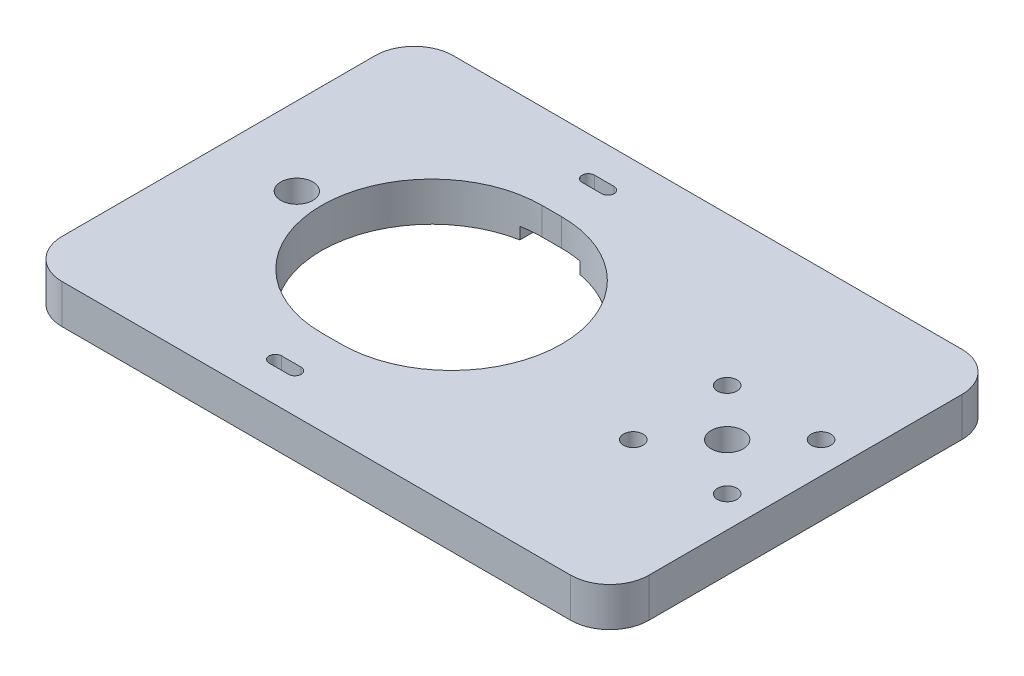
SolidWorks part; units mm, degrees
ref_plane "正面" through (0, 0, 0) normal (0, 0, 1) x (1, 0, 0)
ref_plane "平面" through (0, 0, 0) normal (0, 1, 0) x (1, 0, 0)
ref_plane "右側面" through (0, 0, 0) normal (1, 0, 0) x (0, 0, -1)
sketch "ｽｹｯﾁ1" plane through (0, 0, 0) normal (0, 1, 0) x (1, 0, 0)
  line L1 (-65, -50) -> (65, -50)
  line L2 (-75, -40) -> (-75, 40)
  line L3 (-65, 50) -> (65, 50)
  line L4 (75, -40) -> (75, 40)
  line L5 (-75, -50) -> (75, 50) construction
  line L6 (-75, 50) -> (75, -50) construction
  circle A0 centre (55, 0) radius 4.1
  circle A1 centre (43, 12) radius 2.5
  circle A2 centre (67, 12) radius 2.5
  circle A3 centre (67, -12) radius 2.5
  circle A4 centre (43, -12) radius 2.5
  arc A5 (65, 50) -> (75, 40) centre (65, 40) cw
  arc A6 (65, -50) -> (75, -40) centre (65, -40) ccw
  arc A7 (-65, -50) -> (-75, -40) centre (-65, -40) cw
  arc A8 (-75, 40) -> (-65, 50) centre (-65, 40) cw
  circle A9 centre (-55, 0) radius 4.1
  point P0 (0, 0)
  dimension "D3" = 8.2
  dimension "D9" = 5
  dimension "D10" = 10
  dimension "D11" = 8.2
  dimension "D1" = 150
  dimension "D2" = 100
  dimension "D4" = 20
  dimension "D5" = 24
  dimension "D6" = 24
  dimension "D7" = 12
  dimension "D8" = 12
  dimension "D12" = 20
extrude "ﾎﾞｽ - 押し出し1" add sketch "ｽｹｯﾁ1" along normal blind 10
sketch "ｽｹｯﾁ5" plane through (0, 10, 0) normal (0, 1, 0) x (1, 0, 0)
  line L0 (-27.5, 0) -> (-22.5, 0) construction
  line L3 (-20.5, 0) -> (-15.5, 0) construction
  line L6 (-20.5, 28.2) -> (-15.5, 28.2)
  line L9 (-20.5, -28.2) -> (-15.5, -28.2)
  line L10 (-20.5, 40) -> (-15.5, 40) construction
  line L11 (-20.5, 41.6) -> (-15.5, 41.6)
  line L12 (-20.5, 38.4) -> (-15.5, 38.4)
  line L13 (-20.5, -40) -> (-15.5, -40) construction
  line L14 (-20.5, -38.4) -> (-15.5, -38.4)
  line L15 (-20.5, -41.6) -> (-15.5, -41.6)
  circle A7 centre (-55, 0) radius 4.1 construction
  arc A9 (-20.5, 28.2) -> (-20.5, -28.2) centre (-20.5, 0) ccw
  arc A10 (-15.5, -28.2) -> (-15.5, 28.2) centre (-15.5, 0) ccw
  arc A11 (-20.5, 41.6) -> (-20.5, 38.4) centre (-20.5, 40) ccw
  arc A12 (-15.5, 38.4) -> (-15.5, 41.6) centre (-15.5, 40) ccw
  arc A13 (-20.5, -38.4) -> (-20.5, -41.6) centre (-20.5, -40) ccw
  arc A14 (-15.5, -41.6) -> (-15.5, -38.4) centre (-15.5, -40) ccw
  point P2 (-25, 0)
  point P7 (-18, 0)
  point P14 (-18, 40)
  point P20 (-18, -40)
  point P28 (0, 0)
  dimension "D3" = 7
  dimension "D4" = 5
  dimension "D2" = 30
  dimension "D5" = 28.2
  dimension "D1" = 5
  dimension "D6" = 3.2
  dimension "D7" = 3.2
  dimension "D8" = 40
  dimension "D9" = 40
  dimension "D10" = 5
  dimension "D11" = 5
extrude "ｶｯﾄ - 押し出し3" cut sketch "ｽｹｯﾁ5" against normal up to next
sketch "ｽｹｯﾁ6" plane through (0, 0, 0) normal (0, 1, 0) x (1, 0, 0)
  line L0 (-20.5, 40) -> (-15.5, 40) construction
  line L1 (-20.5, 45.2) -> (-15.5, 45.2)
  line L3 (-20.5, -40) -> (-15.5, -40) construction
  line L5 (-20.5, -45.2) -> (-15.5, -45.2)
  line L6 (-20.5, 0) -> (-15.5, 0) construction
  line L9 (-25.7, 40) -> (-25.7, 27.7164)
  line L10 (-10.3, 40) -> (-10.3, 27.7164)
  line L11 (-25.7, -40) -> (-25.7, -27.7164)
  line L12 (-10.3, -40) -> (-10.3, -27.7164)
  arc A0 (-20.5, 45.2) -> (-25.7, 40) centre (-20.5, 40) ccw
  arc A1 (-10.3, 40) -> (-15.5, 45.2) centre (-15.5, 40) ccw
  arc A2 (-25.7, -40) -> (-20.5, -45.2) centre (-20.5, -40) ccw
  arc A3 (-15.5, -45.2) -> (-10.3, -40) centre (-15.5, -40) ccw
  arc A4 (-25.7, 27.7164) -> (-25.7, -27.7164) centre (-20.5, 0) ccw
  arc A5 (-10.3, -27.7164) -> (-10.3, 27.7164) centre (-15.5, 0) ccw
  circle A6 centre (-55, 0) radius 4.1 construction
  point P3 (-18, 40)
  point P8 (-18, -40)
  point P17 (-18, 0)
  dimension "D2" = 37
  dimension "D4" = 5.2
  dimension "D3" = 28.2
  dimension "D1" = 5
  dimension "D5" = 40
  dimension "D6" = 40
extrude "ｶｯﾄ - 押し出し4" cut sketch "ｽｹｯﾁ6" along normal blind 3
sketch "ｽｹｯﾁ7" plane through (0, 0, 0) normal (0, -1, 0) x (1, 0, 0)
  circle A0 centre (20, 0) radius 5.1
  dimension "D1" = 10.2
  dimension "D2" = 20
extrude "ｶｯﾄ - 押し出し5" cut sketch "ｽｹｯﾁ7" against normal blind 5
